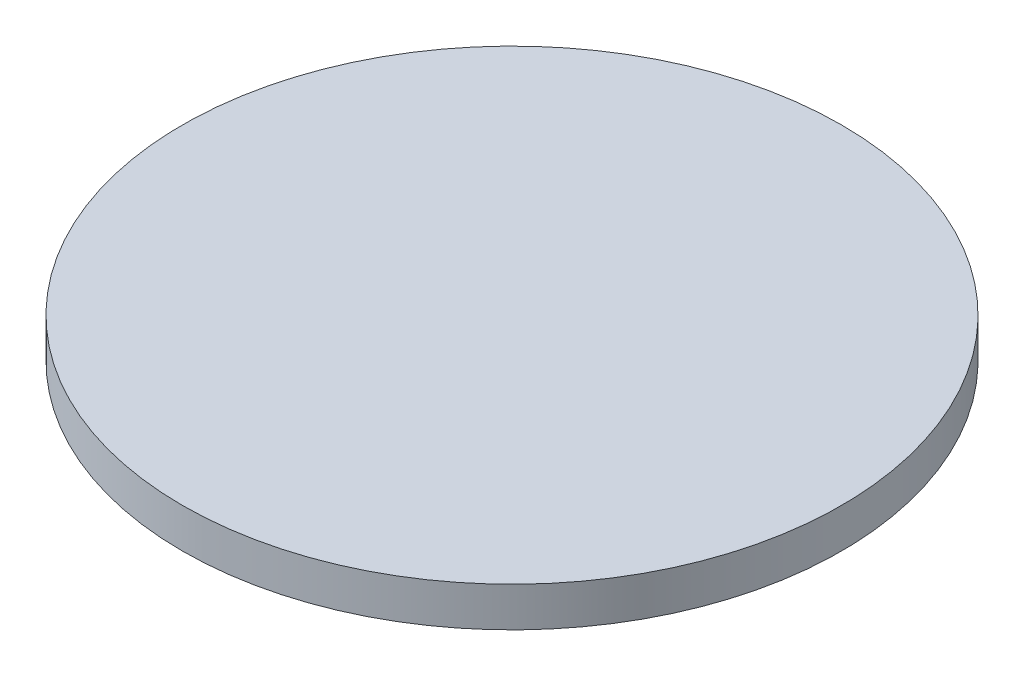
SolidWorks part; units mm, degrees
ref_plane "Front Plane" through (0, 0, 0) normal (0, 0, 1) x (1, 0, 0)
ref_plane "Top Plane" through (0, 0, 0) normal (0, 1, 0) x (1, 0, 0)
ref_plane "Right Plane" through (0, 0, 0) normal (1, 0, 0) x (0, 0, -1)
sketch "Sketch1" plane through (0, 0, 0) normal (0, 1, 0) x (1, 0, 0)
  circle A0 centre (-14.2129, 2.7487) radius 25
  dimension "D1" = 50
extrude "Boss-Extrude1" add sketch "Sketch1" along normal blind 3
